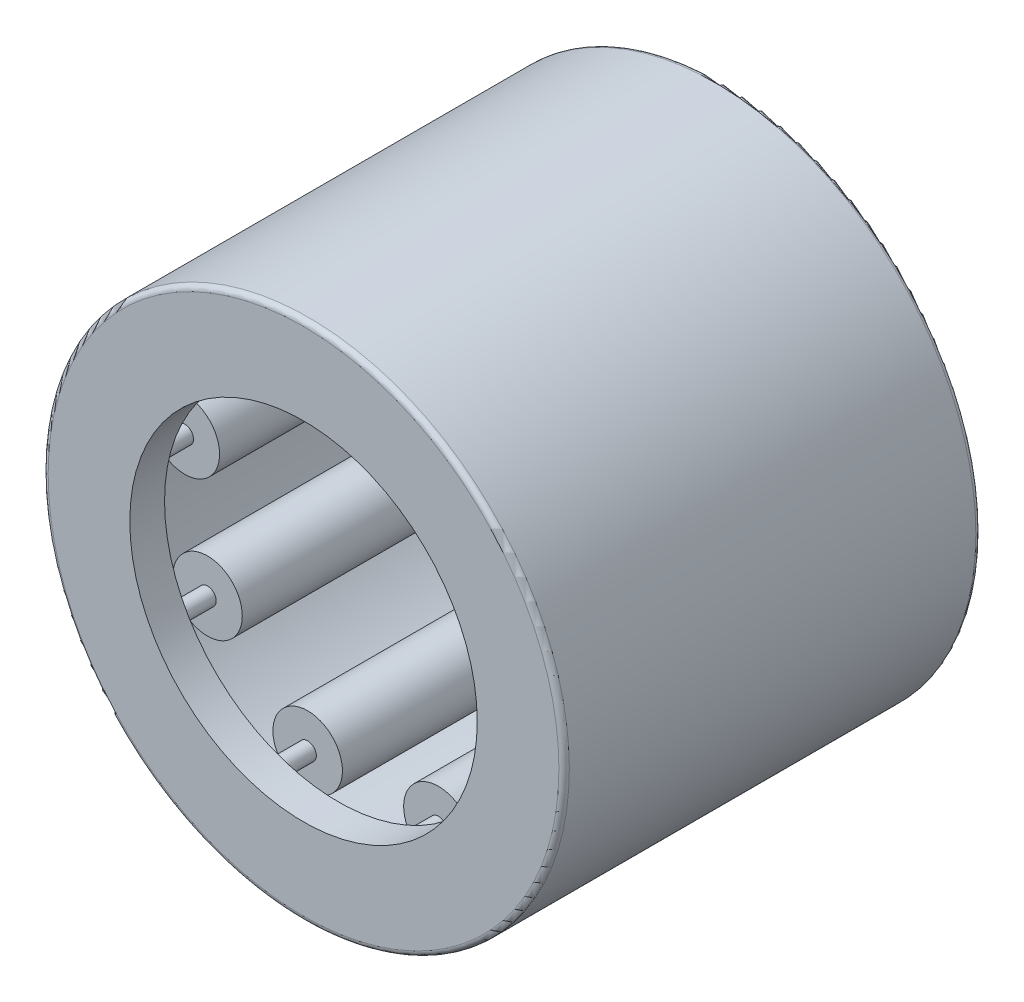
SolidWorks part; units mm, degrees
ref_plane "Front Plane" through (0, 0, 0) normal (0, 0, 1) x (1, 0, 0)
ref_plane "Top Plane" through (0, 0, 0) normal (0, 1, 0) x (1, 0, 0)
ref_plane "Right Plane" through (0, 0, 0) normal (1, 0, 0) x (0, 0, -1)
sketch "Sketch1" plane through (0, 0, 0) normal (1, 0, 0) x (0, 0, -1)
  line L0 (-6.35, 0) -> (6.35, 0) construction
  line L1 (0, 0) -> (0, 7.9375) construction
  line L2 (-6.35, 0) -> (-6.35, 7.9375) construction
  line L3 (-6.35, 7.9375) -> (6.35, 7.9375)
  line L4 (6.35, 7.9375) -> (6.35, 0) construction
  line L5 (6.35, 0) -> (5.2917, 0) construction
  line L6 (5.2917, 0) -> (5.2917, 6.8792) construction
  line L7 (5.2917, 6.8792) -> (-5.2917, 6.8792)
  line L8 (-5.2917, 6.8792) -> (-5.2917, 0) construction
  line L9 (-5.2917, 0) -> (-6.35, 0) construction
  line L10 (-6.35, 7.9375) -> (-6.35, 5.2917)
  line L11 (-6.35, 5.2917) -> (-5.2917, 5.2917)
  line L12 (-5.2917, 5.2917) -> (-5.2917, 6.8792)
  line L13 (5.2917, 7.9375) -> (5.2917, 6.8792) construction
  line L14 (5.2917, 6.8792) -> (5.2917, 5.2917)
  line L15 (5.2917, 5.2917) -> (6.35, 5.2917)
  line L16 (6.35, 5.2917) -> (6.35, 7.9375)
  line L17 (5.2917, 6.8792) -> (5.2917, 5.8208) construction
  line L18 (5.2917, 5.8208) -> (5.2917, 4.7625) construction
  line L19 (5.2917, -6.8792) -> (5.2917, -5.8208) construction
  line L20 (5.2917, -7.9375) -> (5.2917, -6.8792) construction
  line L21 (6.35, -5.2917) -> (6.35, -7.9375) construction
  line L22 (5.2917, -5.2917) -> (6.35, -5.2917) construction
  line L23 (5.2917, -6.8792) -> (5.2917, -5.2917) construction
  line L24 (-5.2917, -5.2917) -> (-5.2917, -6.8792) construction
  line L25 (-6.35, -5.2917) -> (-5.2917, -5.2917) construction
  line L26 (-6.35, -7.9375) -> (-6.35, -5.2917) construction
  line L27 (5.2917, -6.8792) -> (-5.2917, -6.8792) construction
  line L28 (-6.35, -7.9375) -> (6.35, -7.9375) construction
  point P5 (0, 4.7625)
  dimension "Width" = 12.7
  dimension "OD" = 15.875
  dimension "Shaft Dia" = 9.525
revolve "Revolve1" add sketch "Sketch1" angle 360 about L0
sketch "Sketch2" plane through (0, 0, 0) normal (1, 0, 0) x (0, 0, -1)
  line L0 (5.2917, 6.8792) -> (-5.2917, 6.8792) construction
  line L1 (-4.2333, 5.8208) -> (4.2333, 5.8208) construction
  line L2 (-4.2333, 5.8208) -> (-4.2333, 6.8792) construction
  line L3 (-4.2333, 6.8792) -> (4.2333, 6.8792)
  line L4 (4.2333, 5.8208) -> (4.2333, 6.8792) construction
  line L5 (5.2917, 5.2917) -> (6.35, 5.2917) construction
  line L6 (-5.2917, 5.8208) -> (-4.2333, 5.8208) construction
  line L7 (4.2333, 5.8208) -> (5.2917, 5.8208) construction
  line L8 (-6.35, 5.2917) -> (-5.2917, 5.2917) construction
  line L9 (-4.2333, 6.0854) -> (-4.2333, 5.5563) construction
  line L10 (-5.2917, 5.8208) -> (-5.2917, 5.2917) construction
  line L11 (-4.2333, 6.8792) -> (-4.2333, 6.0854)
  line L12 (4.2333, 6.8792) -> (4.2333, 6.0854)
  line L13 (4.2333, 6.0854) -> (-4.2333, 6.0854)
  line L14 (0, 6.8792) -> (0, 4.7625) construction
  line L15 (-5.2917, 5.2917) -> (-5.2917, 6.8792) construction
  line L16 (-4.2333, 5.5563) -> (-5.2917, 5.5562) construction
  line L17 (0, 0) -> (6.35, 0) construction
  line L18 (6.35, -7.9375) -> (6.35, 7.9375) construction
  line L19 (-4.2333, -5.5563) -> (-5.2917, -5.5562) construction
  line L20 (0, -6.8792) -> (0, -4.7625) construction
  line L21 (-5.2917, -5.8208) -> (-5.2917, -5.2917) construction
  line L22 (-4.2333, -6.0854) -> (-4.2333, -5.5563) construction
  line L23 (4.2333, -5.8208) -> (5.2917, -5.8208) construction
  line L24 (-5.2917, -5.8208) -> (-4.2333, -5.8208) construction
  line L25 (4.2333, -5.8208) -> (4.2333, -6.8792) construction
  line L26 (-4.2333, -5.8208) -> (-4.2333, -6.8792) construction
  line L27 (-4.2333, -5.8208) -> (4.2333, -5.8208) construction
  line L28 (4.2333, -6.0854) -> (-4.2333, -6.0854) construction
  line L29 (4.2333, -6.8792) -> (4.2333, -6.0854) construction
  line L30 (-4.2333, -6.8792) -> (-4.2333, -6.0854) construction
  line L31 (-4.2333, -6.8792) -> (4.2333, -6.8792) construction
  point P16 (0, 5.8208)
revolve "Revolve2" add sketch "Sketch2" angle 360 about L1
sketch "Sketch3" plane through (0, 0, 0) normal (1, 0, 0) x (0, 0, -1)
  line L0 (5.2917, 6.8792) -> (5.2917, 5.2917) construction
  line L1 (-5.2917, 5.8208) -> (5.2917, 5.8208)
  line L2 (-5.2917, 5.8208) -> (-5.2917, 6.0854)
  line L3 (-5.2917, 6.0854) -> (5.2917, 6.0854)
  line L4 (5.2917, 5.8208) -> (5.2917, 6.0854)
  line L5 (0, 0) -> (6.35, 0) construction
  line L6 (6.35, -7.9375) -> (6.35, 7.9375) construction
  line L7 (5.2917, -5.8208) -> (5.2917, -6.0854) construction
  line L8 (-5.2917, -6.0854) -> (5.2917, -6.0854) construction
  line L9 (-5.2917, -5.8208) -> (-5.2917, -6.0854) construction
  line L10 (-5.2917, -5.8208) -> (5.2917, -5.8208) construction
revolve "Revolve3" add sketch "Sketch3" angle 360 about L1
ref_axis "Axis1" through (0, 0, -6.35) along (0, 0, 1)
pattern_circular "CirPattern1" count 9 every 40 about axis through (0, 0, -6.35) along (0, 0, 1) of bodies 167 166
fillet "Fillet1" radius 0.1588 2 edges at (7.9375, 0, -6.35) (7.9375, 0, 6.35)
equation "\"Angle@CirPattern1\" = 360/\"Rollers@CirPattern1\""
equation "\"Rollers@CirPattern1\" = \"OD@Sketch1\"*15"
equation "\"D1@Fillet1\" = \"OD@Sketch1\"*.01"
